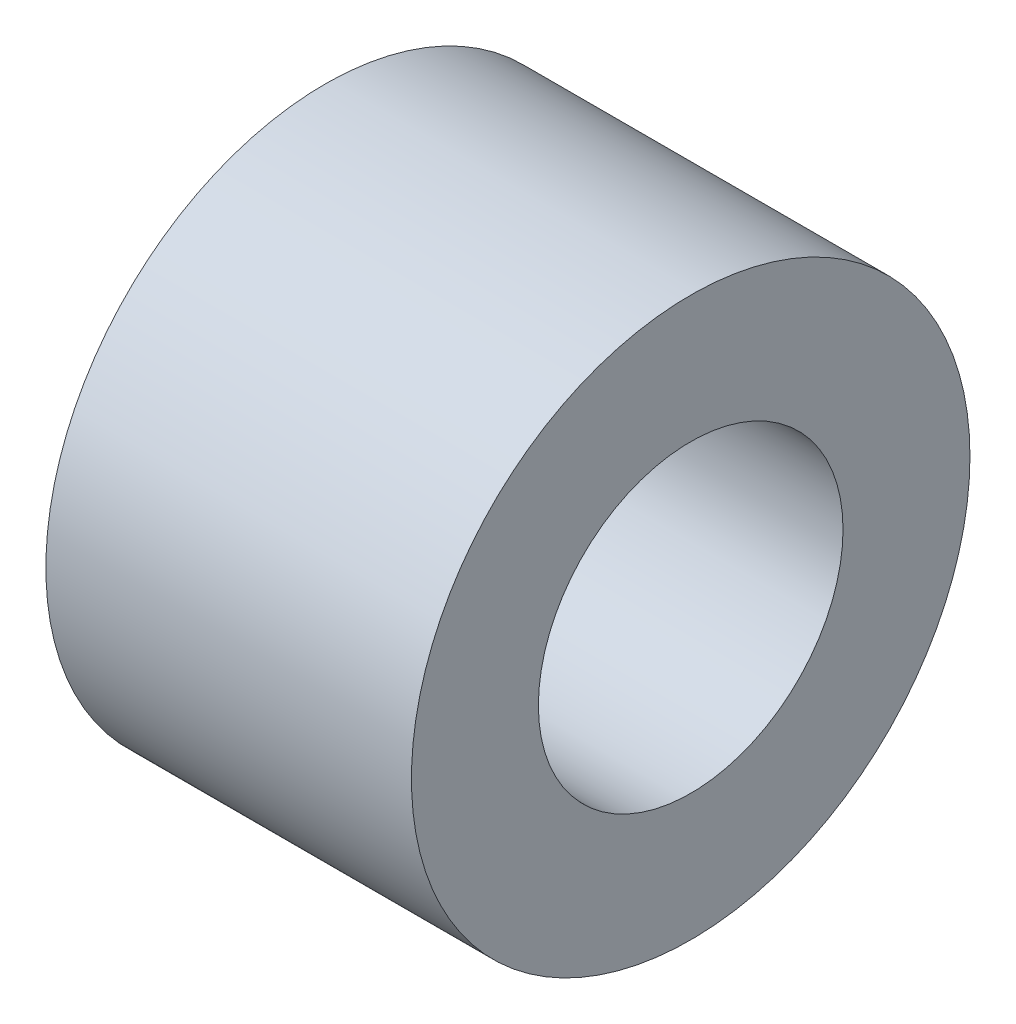
SolidWorks part; units mm, degrees
ref_plane "Front Plane" through (0, 0, 0) normal (0, 0, 1) x (1, 0, 0)
ref_plane "Top Plane" through (0, 0, 0) normal (0, 1, 0) x (1, 0, 0)
ref_plane "Right Plane" through (0, 0, 0) normal (1, 0, 0) x (0, 0, -1)
sketch "Sketch1" plane through (0, 0, 0) normal (1, 0, 0) x (0, 0, -1)
  circle A0 centre (0, 0) radius 1.5
  circle A1 centre (0, 0) radius 2.75
  dimension "D1" = 5.5
  dimension "D2" = 3
extrude "Boss-Extrude1" add sketch "Sketch1" along normal blind 3.6
